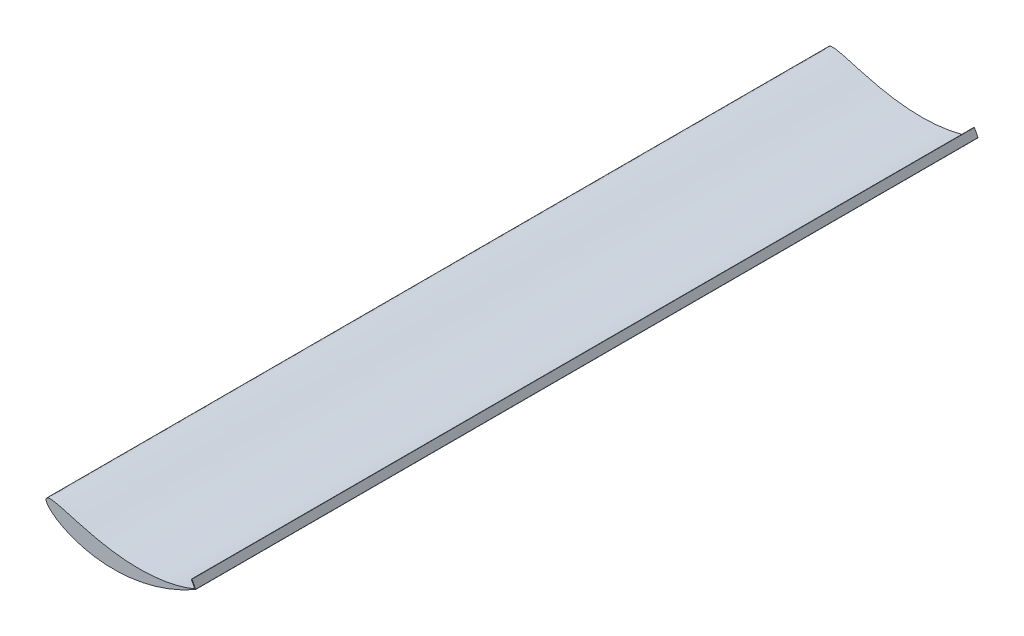
SolidWorks part; units mm, degrees
material "Thornel Mat VMA"
ref_plane "Front Plane" through (0, 0, 0) normal (0, 0, 1) x (1, 0, 0)
ref_plane "Top Plane" through (0, 0, 0) normal (0, 1, 0) x (1, 0, 0)
ref_plane "Right Plane" through (0, 0, 0) normal (1, 0, 0) x (0, 0, -1)
sketch "Sketch2" plane through (0, 0, 0) normal (0, 0, 1) x (1, 0, 0)
  line L0 (191.12, -4.2773) -> (186.601, 4.6434)
  line L1 (186.601, 4.6434) -> (185.7089, 4.1915)
  line L2 (185.7089, 4.1915) -> (190.0401, -4.3584)
  arc A1 (191.12, -4.2773) -> (190.9562, -4.7774) centre (190.7881, -4.4455) cw
  spline S2 degree 3 poles (190.9562, -4.7774) (190.8244, -4.8507) (189.2662, -5.7163) (186.0109, -7.4936) (180.8236, -10.2147) (174.6982, -13.256) (167.5914, -16.5396) (159.4883, -19.9547) (150.394, -23.3651) (140.3485, -26.6129) (129.4336, -29.5249) (117.7796, -31.924) (105.5695, -33.6483) (93.034, -34.5636) (80.4426, -34.5851) (68.0857, -33.687) (56.2533, -31.9099) (45.2123, -29.3578) (35.1866, -26.1865) (26.3435, -22.5854) (18.7877, -18.7593) (12.5633, -14.9069) (7.6602, -11.2053) (4.0276, -7.8032) (1.5737, -4.7963) (0.2015, -2.2527) (-0.2135, -0.069) (0.5971, 1.675) (2.3572, 2.5817) (4.673, 2.9191) (7.6021, 2.8309) (11.0992, 2.3531) (15.1231, 1.539) (19.6227, 0.4401) (24.5519, -0.887) (29.8679, -2.3863) (35.5308, -4.004) (41.5034, -5.6879) (47.7502, -7.3891) (54.2367, -9.0639) (60.9292, -10.6713) (67.7943, -12.1754) (74.7986, -13.5447) (81.9087, -14.7517) (89.091, -15.7747) (96.3114, -16.595) (103.5362, -17.1998) (110.731, -17.5802) (117.8618, -17.7316) (124.8949, -17.6543) (131.7964, -17.3523) (138.5333, -16.8343) (145.0728, -16.1129) (151.3832, -15.2049) (157.4332, -14.13) (163.1927, -12.9124) (168.6325, -11.5795) (173.7246, -10.1624) (178.4413, -8.6936) (182.7568, -7.2105) (186.5826, -5.7747) (188.9582, -4.8122) (190.0401, -4.3584) knots 0.024528 0.024528 0.024528 0.024528 0.025589 0.037068 0.050855 0.066985 0.085458 0.106225 0.12918 0.154149 0.180883 0.209058 0.238272 0.268058 0.297904 0.32727 0.355624 0.382465 0.407356 0.429935 0.449939 0.467202 0.481655 0.493326 0.502345 0.508967 0.513684 0.517466 0.521651 0.527066 0.533952 0.5423 0.552018 0.562982 0.575063 0.588129 0.602057 0.616727 0.632029 0.647858 0.664118 0.680718 0.697573 0.714603 0.731732 0.74889 0.766005 0.783014 0.799852 0.816455 0.832763 0.848714 0.864247 0.879299 0.893808 0.90771 0.920938 0.933424 0.945097 0.955881 0.965701 0.974005 0.974005 0.974005 0.974005
  dimension "D2" = 10
  dimension "D3" = 1
extrude "Boss-Extrude2" add sketch "Sketch2" along normal mid plane 1000 contours S2 L2 L1 L0 A1
